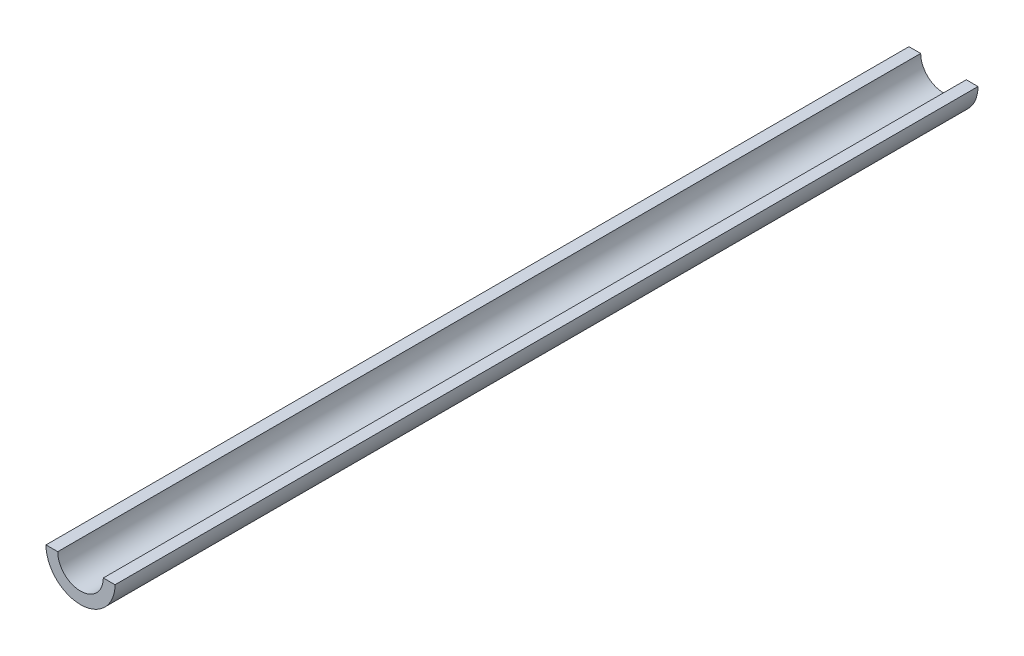
SolidWorks part; units mm, degrees
ref_plane "前视基准面" through (0, 0, 0) normal (0, 0, 1) x (1, 0, 0)
ref_plane "上视基准面" through (0, 0, 0) normal (0, 1, 0) x (1, 0, 0)
ref_plane "右视基准面" through (0, 0, 0) normal (1, 0, 0) x (0, 0, -1)
other "Configuration Table"
sketch "草图1" plane through (0, 0, 0) normal (0, 0, 1) x (1, 0, 0)
  line L1 (6.6, 0) -> (10, 0)
  line L2 (-10, 0) -> (-6.6, 0)
  arc A1 (6.6, 0) -> (-6.6, 0) centre (0, 0) cw
  arc A2 (10, 0) -> (-10, 0) centre (0, 0) cw
  dimension "D1" = 3.4
  dimension "D2" = 10
  dimension "D3" = 3.4
extrude "凸台-拉伸1" add sketch "草图1" along normal blind 250
